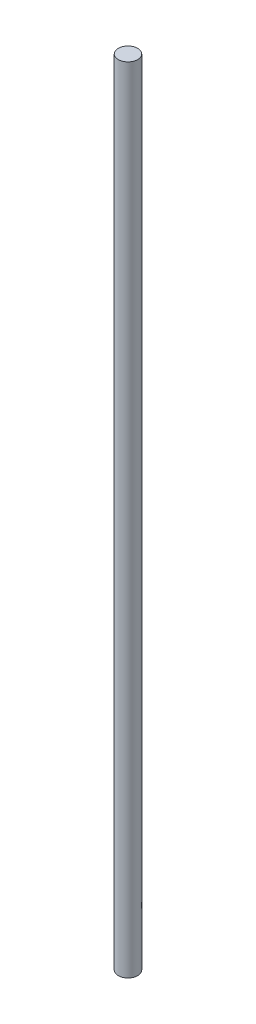
SolidWorks part; units mm, degrees
ref_plane "Front Plane" through (0, 0, 0) normal (0, 0, 1) x (1, 0, 0)
ref_plane "Top Plane" through (0, 0, 0) normal (0, 1, 0) x (1, 0, 0)
ref_plane "Right Plane" through (0, 0, 0) normal (1, 0, 0) x (0, 0, -1)
sketch "Sketch1" plane through (0, 0, 0) normal (0, 1, 0) x (1, 0, 0)
  circle A0 centre (0, 0) radius 4
  dimension "D1" = 8
extrude "Boss-Extrude1" add sketch "Sketch1" along normal up to surface (326 mm away)
